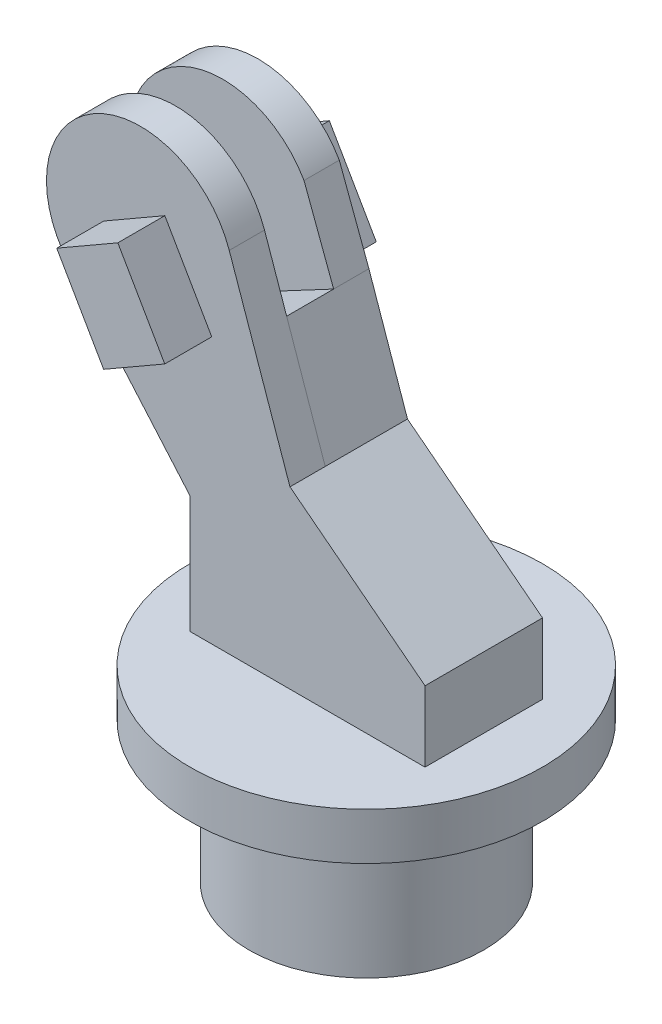
SolidWorks part; units mm, degrees
ref_plane "Front Plane" through (0, 0, 0) normal (0, 0, 1) x (1, 0, 0)
ref_plane "Top Plane" through (0, 0, 0) normal (0, 1, 0) x (1, 0, 0)
ref_plane "Right Plane" through (0, 0, 0) normal (1, 0, 0) x (0, 0, -1)
sketch "Sketch1" plane through (0, 0, 0) normal (0, 0, 1) x (1, 0, 0)
  line L0 (0, 0) -> (0, 76.5101) construction
  line L1 (0, 0) -> (-321.3278, 556.5562) construction
  line L2 (-178.5027, 109.5795) -> (-48.0642, -41.498)
  line L3 (-48.0642, -41.498) -> (-178.5027, 109.5795)
  line L4 (-5.6473, 209.3776) -> (59.9704, 20.8758)
  line L5 (59.9704, 20.8758) -> (-5.6473, 209.3776)
  circle A0 centre (-101.6, 175.9764) radius 101.6
  circle A1 centre (0, 0) radius 63.5
  point P3 (-31.75, 54.9926)
  point P5 (-101.6, 175.9764)
  dimension "D4" = 203.2
  dimension "D5" = 127
  dimension "D1" = 30
  dimension "D2" = 63.5
  dimension "D3" = 203.2
extrude "Boss-Extrude3" add sketch "Sketch1" along normal blind 38.1 contours A1 L4 A0 L2
sketch "Sketch2" plane through (0, 0, 38.1) normal (0, 0, 1) x (1, 0, 0)
  circle A0 centre (-101.6, 175.9764) radius 101.6
  circle A1 centre (0, 0) radius 63.5
  dimension "D1" = 203.2
  dimension "D2" = 127
extrude "Boss-Extrude4" add sketch "Sketch2" against normal blind 38.1
sketch "Sketch3" plane through (0, 0, 38.1) normal (0, 0, 1) x (1, 0, 0)
  line L0 (-48.0642, -41.498) -> (-48.0642, -168.498)
  line L1 (-48.0642, -168.498) -> (205.9358, -168.498)
  line L2 (205.9358, -168.498) -> (205.9358, -92.298)
  line L3 (205.9358, -92.298) -> (59.9704, 20.8758)
  line L6 (-178.5027, 109.5795) -> (-48.0642, -41.498)
  line L7 (59.9704, 20.8758) -> (-5.6473, 209.3776)
  arc A2 (-48.0642, -41.498) -> (59.9704, 20.8758) centre (0, 0) ccw
  arc A3 (-5.6473, 209.3776) -> (-178.5027, 109.5795) centre (-101.6, 175.9764) ccw
  arc A4 (-48.0642, -41.498) -> (59.9704, 20.8758) centre (0, 0) ccw
  dimension "D1" = 127
  dimension "D2" = 254
  dimension "D3" = 76.2
  dimension "D4" = 0
extrude "Boss-Extrude5" add sketch "Sketch3" against normal blind 127
sketch "Sketch4" plane through (0, 0, 0) normal (0, 0, -1) x (-1, 0, 0)
  line L0 (-60.0147, 20.7482) -> (-18.2633, 140.689)
  line L1 (5.6473, 209.3776) -> (-59.9704, 20.8758) construction
  line L2 (51.7739, -36.7657) -> (134.9852, 59.1763)
  line L3 (178.5027, 109.5795) -> (48.0642, -41.498) construction
  line L4 (-18.2633, 140.689) -> (134.9852, 59.1763)
  arc A0 (-60.0147, 20.7482) -> (51.7739, -36.7657) centre (0, 0) ccw
  arc A1 (-59.9704, 20.8758) -> (48.0642, -41.498) centre (0, 0) ccw construction
  dimension "D1" = 127
  dimension "D2" = 127
extrude "Boss-Extrude7" add sketch "Sketch4" along normal blind 88.9
ref_plane "Plane2" through (0, 0, -88.9) normal (0, 0, -1) x (-1, 0, 0)
ref_plane "Plane3" through (0, -168.498, 0) normal (0, -1, 0) x (-1, 0, 0)
sketch "Sketch9" plane through (0, -168.498, 0) normal (0, -1, 0) x (-1, 0, 0)
  line L0 (48.0642, -38.1) -> (-205.9358, -38.1) construction
  line L1 (48.0642, -38.1) -> (48.0642, 0) construction
  circle A0 centre (-78.9358, 25.4) radius 190.5
  point P0 (-78.9358, 25.4)
  dimension "D3" = 381
  dimension "D1" = 63.5
  dimension "D2" = 127
sketch "Sketch11" plane through (0, 0, -88.9) normal (0, 0, -1) x (-1, 0, 0)
  line L0 (13.737, 226.314) -> (-18.2633, 140.689)
  line L1 (-18.2633, 140.689) -> (134.9852, 59.1763)
  line L2 (134.9852, 59.1763) -> (189.463, 125.6388)
  arc A0 (189.463, 125.6388) -> (13.737, 226.314) centre (101.6, 175.9764) ccw
extrude "Boss-Extrude8" add sketch "Sketch11" against normal blind 38.1
extrude "Boss-Extrude9" add sketch "Sketch9" along normal blind 50.8
sketch "Sketch15" plane through (0, -219.298, 0) normal (0, -1, 0) x (1, 0, 0)
  circle A0 centre (78.6921, -25.7623) radius 127
  point P0 (78.6921, -25.7623)
  dimension "D1" = 254
extrude "Boss-Extrude10" add sketch "Sketch15" along normal blind 152.4
sketch "Sketch16" plane through (0, 0, -50.8) normal (0, 0, 1) x (1, 0, 0)
  circle A0 centre (-101.6, 175.9764) radius 12.7
  dimension "D1" = 25.4
extrude "Boss-Extrude11" add sketch "Sketch16" along normal blind 50.8
sketch "Sketch17" plane through (0, -371.698, 0) normal (0, -1, 0) x (1, 0, 0)
  circle A0 centre (78.6921, -25.7623) radius 63.5
  dimension "D1" = 127
extrude "Cut-Extrude1" cut sketch "Sketch17" against normal blind 25.4
sketch "Sketch19" plane through (0, 0, 38.1) normal (0, 0, 1) x (1, 0, 0)
  line L0 (0, 0) -> (-151.9376, 263.8393) construction
  line L1 (-24.5649, 119.0037) -> (-75.2672, 207.0481)
  line L2 (-24.5649, 119.0037) -> (-90.5983, 80.9769)
  line L3 (-75.2672, 207.0481) -> (-141.3006, 169.0214)
  line L4 (-90.5983, 80.9769) -> (-141.3006, 169.0214)
  line L5 (-24.5649, 119.0037) -> (-141.3006, 169.0214) construction
  line L6 (-75.2672, 207.0481) -> (-90.5983, 80.9769) construction
  arc A0 (-13.737, 226.314) -> (-189.463, 125.6388) centre (-101.6, 175.9764) ccw construction
  point P6 (0, 0)
  point P7 (-82.9327, 144.0125)
  dimension "D1" = 76.2
  dimension "D2" = 101.6
extrude "Boss-Extrude12" add sketch "Sketch19" along normal blind 50.8
ref_plane "Plane4" through (0, 0, -25.4) normal (0, 0, -1) x (-1, 0, 0)
mirror "Mirror1" about plane through (0, 0, -25.4) normal (0, 0, -1) of "Boss-Extrude12"
